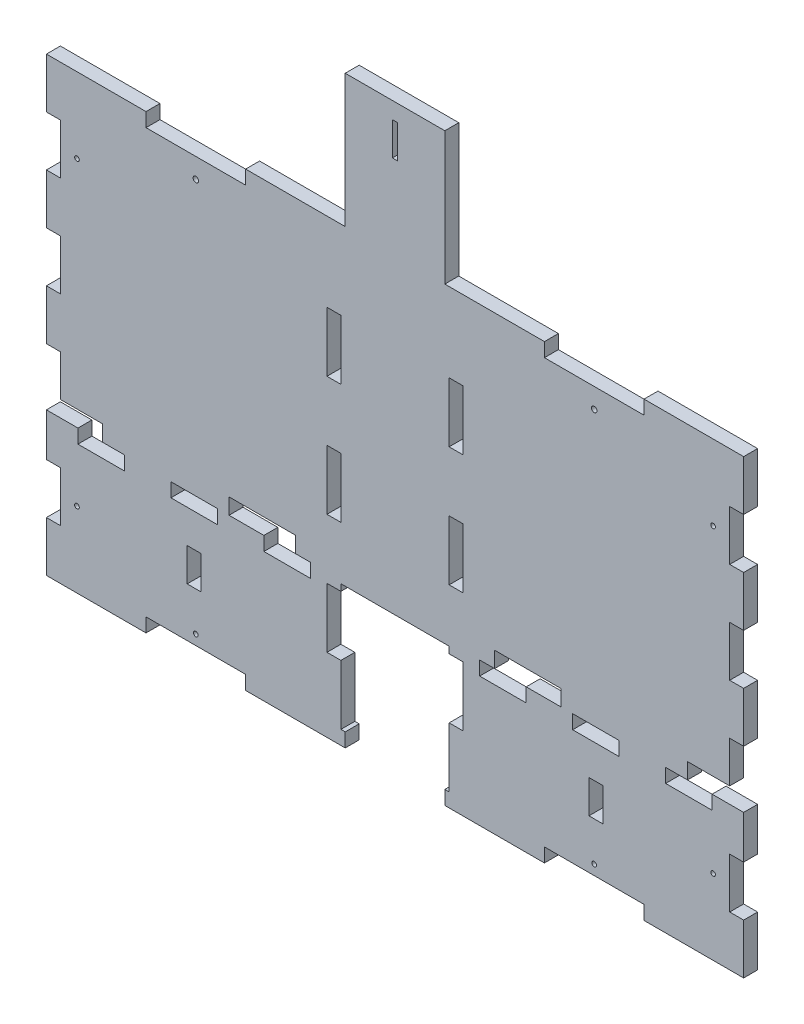
SolidWorks part; units mm, degrees
ref_plane "Front Plane" through (0, 0, 0) normal (0, 0, 1) x (1, 0, 0)
ref_plane "Top Plane" through (0, 0, 0) normal (0, 1, 0) x (1, 0, 0)
ref_plane "Right Plane" through (0, 0, 0) normal (1, 0, 0) x (0, 0, -1)
sketch "Sketch1" plane through (0, 0, 0) normal (0, 0, 1) x (1, 0, 0)
  line L1 (-127.8759, 88.4641) -> (138.8241, 88.4641)
  line L2 (-127.8759, 88.4641) -> (-127.8759, -84.2559)
  line L3 (-127.8759, -84.2559) -> (138.8241, -84.2559)
  line L4 (138.8241, 88.4641) -> (138.8241, -84.2559)
  dimension "D1" = 266.7
  dimension "D2" = 172.72
extrude "Boss-Extrude1" add sketch "Sketch1" along normal blind 5.334
sketch "Sketch2" plane through (0, 0, 5.334) normal (0, 0, 1) x (1, 0, 0)
  line L0 (-127.8759, -84.2559) -> (138.8241, -84.2559) construction
  line L1 (-89.7759, -84.2559) -> (-51.6759, -84.2559)
  line L2 (-89.7759, -84.2559) -> (-89.7759, -78.9219)
  line L3 (-89.7759, -78.9219) -> (-51.6759, -78.9219)
  line L4 (-51.6759, -84.2559) -> (-51.6759, -78.9219)
  line L5 (-89.7759, -78.9219) -> (-127.8759, -78.9219) construction
  line L6 (-13.5759, -84.2559) -> (24.5241, -84.2559)
  line L7 (-13.5759, -84.2559) -> (-13.5759, -78.9219)
  line L8 (-13.5759, -78.9219) -> (24.5241, -78.9219)
  line L9 (24.5241, -84.2559) -> (24.5241, -78.9219)
  line L10 (62.6241, -84.2559) -> (100.7241, -84.2559)
  line L11 (62.6241, -84.2559) -> (62.6241, -78.9219)
  line L12 (62.6241, -78.9219) -> (100.7241, -78.9219)
  line L13 (100.7241, -84.2559) -> (100.7241, -78.9219)
  line L14 (-127.8759, 88.4641) -> (-127.8759, -84.2559) construction
  line L15 (-51.6759, -78.9219) -> (-13.5759, -78.9219) construction
  line L16 (24.5241, -78.9219) -> (62.6241, -78.9219) construction
  line L17 (62.6241, -78.9219) -> (62.364, -79.7896) construction
  line L18 (100.7241, -78.9219) -> (138.8241, -78.9219) construction
  line L19 (138.8241, -84.2559) -> (138.8241, 88.4641) construction
  line L20 (-127.8759, 2.1041) -> (138.8241, 2.1041) construction
  line L21 (100.7241, 88.4641) -> (100.7241, 83.1301)
  line L22 (62.6241, 83.1301) -> (100.7241, 83.1301)
  line L23 (62.6241, 88.4641) -> (62.6241, 83.1301)
  line L24 (24.5241, 88.4641) -> (24.5241, 83.1301)
  line L25 (-13.5759, 83.1301) -> (24.5241, 83.1301)
  line L26 (-13.5759, 88.4641) -> (-13.5759, 83.1301)
  line L27 (-51.6759, 88.4641) -> (-51.6759, 83.1301)
  line L28 (-89.7759, 83.1301) -> (-51.6759, 83.1301)
  line L29 (-89.7759, 88.4641) -> (-89.7759, 83.1301)
  line L30 (62.6241, 88.4641) -> (100.7241, 88.4641)
  line L31 (-13.5759, 88.4641) -> (24.5241, 88.4641)
  line L32 (-89.7759, 88.4641) -> (-51.6759, 88.4641)
  dimension "D1" = 5.334
extrude "Cut-Extrude1" cut sketch "Sketch2" against normal through all
sketch "Sketch5" plane through (0, 0, 5.334) normal (0, 0, 1) x (1, 0, 0)
  line L0 (5.4741, 83.1301) -> (5.4741, -78.9219) construction
  line L1 (-13.5759, 83.1301) -> (24.5241, 83.1301) construction
  line L2 (24.5241, -78.9219) -> (-13.5759, -78.9219) construction
  line L3 (43.5741, -23.2959) -> (43.5741, -29.3919)
  line L4 (-58.0259, -23.2959) -> (-32.6259, -23.2959)
  line L5 (-58.0259, -23.2959) -> (-58.0259, -29.3919)
  line L6 (-58.0259, -29.3919) -> (-32.6259, -29.3919)
  line L7 (-32.6259, -23.2959) -> (-32.6259, -29.3919)
  line L8 (68.9741, -29.3919) -> (43.5741, -29.3919)
  line L9 (68.9741, -23.2959) -> (68.9741, -29.3919)
  line L10 (68.9741, -23.2959) -> (43.5741, -23.2959)
  line L11 (43.5741, -23.2959) -> (-32.6259, -23.2959) construction
  line L12 (-32.6259, -29.3919) -> (43.5741, -29.3919) construction
  line L13 (-127.8759, 88.4641) -> (-127.8759, -84.2559) construction
  line L14 (-106.3983, -23.2959) -> (-127.8759, -23.2959)
  line L15 (-106.3983, -23.2959) -> (-106.3983, -29.3919)
  line L16 (-106.3983, -29.3919) -> (-127.8759, -29.3919)
  line L17 (-127.8759, -23.2959) -> (-127.8759, -29.3919)
  line L18 (117.3465, -29.3919) -> (138.8241, -29.3919)
  line L19 (138.8241, -23.2959) -> (138.8241, -29.3919)
  line L20 (117.3465, -23.2959) -> (138.8241, -23.2959)
  line L21 (117.3465, -23.2959) -> (117.3465, -29.3919)
  line L22 (-51.6759, -78.9219) -> (-89.7759, -78.9219) construction
  dimension "D2" = 25.4
  dimension "D3" = 38.1
  dimension "D1" = 6.096
  dimension "D4" = 49.53
  dimension "D5" = 0
  dimension "D6" = 0
extrude "Cut-Extrude3" cut sketch "Sketch5" against normal through all
sketch "Sketch9" plane through (0, 0, 5.334) normal (0, 0, 1) x (1, 0, 0)
  line L0 (-127.8759, 88.4641) -> (-127.8759, -23.2959) construction
  line L1 (-127.8759, -65.0647) -> (-122.5419, -65.0647)
  line L2 (-127.8759, -65.0647) -> (-127.8759, -45.8736)
  line L3 (-127.8759, -45.8736) -> (-122.5419, -45.8736)
  line L4 (-122.5419, -65.0647) -> (-122.5419, -45.8736)
  line L5 (-122.5419, 69.273) -> (-122.5419, 88.4641) construction
  line L6 (-127.8759, -26.6825) -> (-122.5419, -26.6825)
  line L7 (-127.8759, -26.6825) -> (-127.8759, -7.4914)
  line L8 (-127.8759, -7.4914) -> (-122.5419, -7.4914)
  line L9 (-122.5419, -26.6825) -> (-122.5419, -7.4914)
  line L10 (-127.8759, 11.6997) -> (-122.5419, 11.6997)
  line L11 (-127.8759, 11.6997) -> (-127.8759, 30.8908)
  line L12 (-127.8759, 30.8908) -> (-122.5419, 30.8908)
  line L13 (-122.5419, 11.6997) -> (-122.5419, 30.8908)
  line L14 (-127.8759, 50.0819) -> (-122.5419, 50.0819)
  line L15 (-127.8759, 50.0819) -> (-127.8759, 69.273)
  line L16 (-127.8759, 69.273) -> (-122.5419, 69.273)
  line L17 (-122.5419, 50.0819) -> (-122.5419, 69.273)
  line L18 (-89.7759, 88.4641) -> (-127.8759, 88.4641) construction
  line L19 (-122.5419, 50.0819) -> (-122.5419, 30.8908) construction
  line L20 (-122.5419, 11.6997) -> (-122.5419, -7.4914) construction
  line L21 (-122.5419, -26.6825) -> (-122.5419, -45.8736) construction
  line L22 (-122.5419, -65.0647) -> (-122.5419, -84.2559) construction
  line L23 (-127.8759, -84.2559) -> (-89.7759, -84.2559) construction
  line L24 (5.4741, 83.1301) -> (5.4741, -78.9219) construction
  line L25 (-13.5759, 83.1301) -> (24.5241, 83.1301) construction
  line L26 (24.5241, -78.9219) -> (-13.5759, -78.9219) construction
  line L27 (133.4901, -65.0647) -> (133.4901, -84.2559) construction
  line L28 (133.4901, -26.6825) -> (133.4901, -45.8736) construction
  line L29 (133.4901, 11.6997) -> (133.4901, -7.4914) construction
  line L30 (133.4901, 50.0819) -> (133.4901, 30.8908) construction
  line L31 (133.4901, 69.273) -> (133.4901, 88.4641) construction
  line L32 (133.4901, 50.0819) -> (133.4901, 69.273)
  line L33 (138.8241, 69.273) -> (133.4901, 69.273)
  line L34 (138.8241, 50.0819) -> (138.8241, 69.273)
  line L35 (138.8241, 50.0819) -> (133.4901, 50.0819)
  line L36 (133.4901, 11.6997) -> (133.4901, 30.8908)
  line L37 (138.8241, 30.8908) -> (133.4901, 30.8908)
  line L38 (138.8241, 11.6997) -> (138.8241, 30.8908)
  line L39 (138.8241, 11.6997) -> (133.4901, 11.6997)
  line L40 (133.4901, -26.6825) -> (133.4901, -7.4914)
  line L41 (138.8241, -7.4914) -> (133.4901, -7.4914)
  line L42 (138.8241, -26.6825) -> (138.8241, -7.4914)
  line L43 (138.8241, -26.6825) -> (133.4901, -26.6825)
  line L44 (133.4901, -65.0647) -> (133.4901, -45.8736)
  line L45 (138.8241, -45.8736) -> (133.4901, -45.8736)
  line L46 (138.8241, -65.0647) -> (138.8241, -45.8736)
  line L47 (138.8241, -65.0647) -> (133.4901, -65.0647)
  dimension "D1" = 5.334
extrude "Cut-Extrude7" cut sketch "Sketch9" against normal through all
sketch "Sketch10" plane through (0, 88.4641, 0) normal (0, 1, 0) x (1, 0, 0)
  line L1 (24.5241, -5.334) -> (62.6241, -5.334)
  line L2 (24.5241, -5.334) -> (24.5241, 0)
  line L3 (24.5241, 0) -> (62.6241, 0)
  line L4 (62.6241, -5.334) -> (62.6241, 0)
extrude "Boss-Extrude2" add sketch "Sketch10" along normal blind 50.8
sketch "Sketch11" plane through (0, 0, 0) normal (0, 0, -1) x (-1, 0, 0)
  line L0 (-24.5241, 83.1301) -> (-24.5241, 139.2641) construction
  line L1 (-24.5241, 88.4641) -> (-31.1281, 88.4641)
  line L2 (-24.5241, 88.4641) -> (-24.5241, 129.1041)
  line L3 (-24.5241, 129.1041) -> (-31.1281, 129.1041)
  line L4 (-31.1281, 88.4641) -> (-31.1281, 129.1041)
  line L5 (13.5759, 88.4641) -> (51.6759, 88.4641) construction
  dimension "D1" = 6.604
  dimension "D2" = 40.64
  dimension "D3" = 0
extrude "Cut-Extrude8" cut sketch "Sketch11" against normal through all
sketch "Sketch12" plane through (0, 0, 5.334) normal (0, 0, 1) x (1, 0, 0)
  line L0 (62.6241, 139.2641) -> (62.6241, 83.1301) construction
  circle A0 centre (43.5741, 130.4765) radius 3.81
  dimension "D1" = 19.05
extrude "Cut-Extrude9" cut sketch "Sketch12" against normal through all
sketch "Sketch15" plane through (0, 0, 5.334) normal (0, 0, 1) x (1, 0, 0)
  line L1 (31.1281, 129.1041) -> (24.5241, 129.1041)
  line L2 (31.1281, 129.1041) -> (31.1281, 139.2641)
  line L3 (31.1281, 139.2641) -> (24.5241, 139.2641)
  line L4 (24.5241, 129.1041) -> (24.5241, 139.2641)
extrude "Cut-Extrude12" cut sketch "Sketch15" against normal through all
sketch "Sketch18" plane through (0, 0, 5.334) normal (0, 0, 1) x (1, 0, 0)
  line L0 (24.5241, 83.1301) -> (24.5241, 148.9274) construction
  line L1 (31.1281, 139.2641) -> (62.6241, 139.2641) construction
  line L2 (-13.5759, 83.1301) -> (24.5241, 83.1301)
  line L3 (-13.5759, 83.1301) -> (-13.5759, 139.2641)
  line L4 (-13.5759, 139.2641) -> (24.5241, 139.2641)
  line L5 (24.5241, 83.1301) -> (24.5241, 139.2641)
  dimension "D1" = 0
extrude "Boss-Extrude3" add sketch "Sketch18" against normal blind 5.334
sketch "Sketch19" plane through (0, 0, 5.334) normal (0, 0, 1) x (1, 0, 0)
  line L1 (31.1281, 88.4641) -> (65.8849, 88.4641)
  line L2 (31.1281, 88.4641) -> (31.1281, 143.4078)
  line L3 (31.1281, 143.4078) -> (65.8849, 143.4078)
  line L4 (65.8849, 88.4641) -> (65.8849, 143.4078)
extrude "Cut-Extrude15" cut sketch "Sketch19" against normal through all
sketch "Sketch21" plane through (0, 0, 5.334) normal (0, 0, 1) x (1, 0, 0)
  line L0 (133.4901, 59.6775) -> (-122.5419, 59.6775) construction
  line L1 (133.4901, 69.273) -> (133.4901, 50.0819) construction
  line L2 (-122.5419, 50.0819) -> (-122.5419, 69.273) construction
  line L3 (-122.5419, -55.4692) -> (133.4901, -55.4692) construction
  line L4 (-122.5419, -65.0647) -> (-122.5419, -45.8736) construction
  line L5 (133.4901, -45.8736) -> (133.4901, -65.0647) construction
  line L6 (138.8241, 2.1041) -> (-127.8759, 2.1041) construction
  line L7 (138.8241, -7.4914) -> (138.8241, 11.6997) construction
  line L8 (-127.8759, 11.6997) -> (-127.8759, -7.4914) construction
  line L9 (5.4741, 139.2641) -> (5.4741, -78.9219) construction
  line L10 (24.5241, 139.2641) -> (-13.5759, 139.2641) construction
  line L11 (24.5241, -78.9219) -> (-13.5759, -78.9219) construction
  circle A0 centre (127.1401, 59.6775) radius 0.889
  circle A1 centre (-116.1919, 59.6775) radius 0.889
  circle A2 centre (-116.1919, -55.4692) radius 0.889
  circle A3 centre (127.1401, -55.4692) radius 0.889
  dimension "D1" = 1.778
  dimension "D2" = 0
  dimension "D3" = 6.35
extrude "Cut-Extrude17" cut sketch "Sketch21" against normal through all
sketch "Sketch23" plane through (0, 0, 0) normal (0, 0, -1) x (-1, 0, 0)
  line L0 (-81.6741, 83.1301) -> (-81.6741, 61.0847) construction
  line L1 (-62.6241, 83.1301) -> (-100.7241, 83.1301) construction
  line L2 (-5.4741, 139.2641) -> (-5.4741, 93.6801) construction
  line L3 (-24.5241, 139.2641) -> (13.5759, 139.2641) construction
  circle A0 centre (-81.6741, 75.5101) radius 1.0477
  circle A1 centre (70.7259, 75.5101) radius 1.0477
  dimension "D1" = 2.0955
  dimension "D2" = 0
  dimension "D3" = 7.62
extrude "Cut-Extrude19" cut sketch "Sketch23" against normal through all
sketch "Sketch25" plane through (0, 0, 0) normal (0, 0, -1) x (-1, 0, 0)
  line L1 (-126.7591, -29.3919) -> (-108.9791, -29.3919)
  line L2 (-126.7591, -29.3919) -> (-126.7591, -34.7259)
  line L3 (-126.7591, -34.7259) -> (-108.9791, -34.7259)
  line L4 (-108.9791, -29.3919) -> (-108.9791, -34.7259)
  line L5 (-138.8241, -45.8736) -> (-138.8241, -29.3919) construction
  line L6 (-91.1991, -34.7259) -> (-73.4191, -34.7259)
  line L7 (-73.4191, -29.3919) -> (-73.4191, -34.7259)
  line L8 (-91.1991, -29.3919) -> (-73.4191, -29.3919)
  line L9 (-91.1991, -29.3919) -> (-91.1991, -34.7259)
  line L10 (-55.6391, -34.7259) -> (-37.8591, -34.7259)
  line L11 (-37.8591, -29.3919) -> (-37.8591, -34.7259)
  line L12 (-55.6391, -29.3919) -> (-37.8591, -29.3919)
  line L13 (-55.6391, -29.3919) -> (-55.6391, -34.7259)
  line L14 (-5.4741, -78.9219) -> (-5.4741, 139.2641) construction
  line L15 (-24.5241, -78.9219) -> (13.5759, -78.9219) construction
  line L16 (-24.5241, 139.2641) -> (13.5759, 139.2641) construction
  line L17 (44.6909, -29.3919) -> (44.6909, -34.7259)
  line L18 (44.6909, -29.3919) -> (26.9109, -29.3919)
  line L19 (26.9109, -29.3919) -> (26.9109, -34.7259)
  line L20 (44.6909, -34.7259) -> (26.9109, -34.7259)
  line L21 (115.8109, -29.3919) -> (98.0309, -29.3919)
  line L22 (115.8109, -29.3919) -> (115.8109, -34.7259)
  line L23 (115.8109, -34.7259) -> (98.0309, -34.7259)
  line L24 (98.0309, -29.3919) -> (98.0309, -34.7259)
  line L25 (80.2509, -29.3919) -> (80.2509, -34.7259)
  line L26 (80.2509, -29.3919) -> (62.4709, -29.3919)
  line L27 (62.4709, -29.3919) -> (62.4709, -34.7259)
  line L28 (80.2509, -34.7259) -> (62.4709, -34.7259)
  line L29 (-43.5741, -29.3919) -> (-68.9741, -29.3919) construction
  dimension "D5" = 0
  dimension "D1" = 12.065
  dimension "D2" = 17.78
  dimension "D3" = 5.334
  dimension "D4" = 3
extrude "Cut-Extrude20" cut sketch "Sketch25" against normal through all
sketch "Sketch26" plane through (0, 0, 0) normal (0, 0, -1) x (-1, 0, 0)
  line L0 (-91.1991, -34.7259) -> (-73.4191, -34.7259) construction
  line L1 (-84.9761, -47.4259) -> (-79.6421, -47.4259)
  line L2 (-84.9761, -47.4259) -> (-84.9761, -60.1259)
  line L3 (-84.9761, -60.1259) -> (-79.6421, -60.1259)
  line L4 (-79.6421, -47.4259) -> (-79.6421, -60.1259)
  line L5 (-82.3091, -34.7259) -> (-82.3091, -84.0309) construction
  line L6 (-5.4741, -78.9219) -> (-5.4741, -42.666) construction
  line L7 (-24.5241, -78.9219) -> (13.5759, -78.9219) construction
  line L8 (68.6939, -47.4259) -> (68.6939, -60.1259)
  line L9 (74.0279, -60.1259) -> (68.6939, -60.1259)
  line L10 (74.0279, -47.4259) -> (74.0279, -60.1259)
  line L11 (74.0279, -47.4259) -> (68.6939, -47.4259)
  point P4 (-82.3091, -34.7259)
  dimension "D3" = 5.334
  dimension "D1" = 12.7
  dimension "D2" = 12.7
  dimension "D4" = 2.667
extrude "Cut-Extrude21" cut sketch "Sketch26" against normal through all
sketch "Sketch27" plane through (0, 0, 0) normal (0, 0, -1) x (-1, 0, 0)
  line L0 (-24.5241, -78.9219) -> (13.5759, -78.9219) construction
  line L1 (-26.1751, -78.9219) -> (15.2269, -78.9219)
  line L2 (-26.1751, -78.9219) -> (-26.1751, -30.6619)
  line L3 (-26.1751, -30.6619) -> (15.2269, -30.6619)
  line L4 (15.2269, -78.9219) -> (15.2269, -30.6619)
  line L5 (13.5759, -82.3391) -> (-24.5241, -82.3391) construction
  line L6 (13.5759, -78.9219) -> (13.5759, -84.2559) construction
  line L7 (-24.5241, -84.2559) -> (-24.5241, -78.9219) construction
  line L8 (-5.4741, -82.3391) -> (-5.4741, 2.254) construction
  dimension "D1" = 41.402
  dimension "D2" = 48.26
  dimension "D3" = 0
  dimension "D4" = 20.701
extrude "Cut-Extrude22" cut sketch "Sketch27" against normal through all
sketch "Sketch28" plane through (0, 0, 0) normal (0, 0, -1) x (-1, 0, 0)
  line L0 (-26.1751, -30.6619) -> (-26.1751, -78.9219) construction
  line L1 (-26.1751, -56.0619) -> (-31.5091, -56.0619)
  line L2 (-26.1751, -56.0619) -> (-26.1751, -33.2019)
  line L3 (-26.1751, -33.2019) -> (-31.5091, -33.2019)
  line L4 (-31.5091, -56.0619) -> (-31.5091, -33.2019)
  line L5 (-26.1751, -78.9219) -> (-37.6658, -78.9219) construction
  line L6 (-26.1751, -10.3419) -> (-31.5091, -10.3419)
  line L7 (-26.1751, -10.3419) -> (-26.1751, 12.5181)
  line L8 (-26.1751, 12.5181) -> (-31.5091, 12.5181)
  line L9 (-31.5091, -10.3419) -> (-31.5091, 12.5181)
  line L10 (-26.1751, 35.3781) -> (-31.5091, 35.3781)
  line L11 (-26.1751, 35.3781) -> (-26.1751, 58.2381)
  line L12 (-26.1751, 58.2381) -> (-31.5091, 58.2381)
  line L13 (-31.5091, 35.3781) -> (-31.5091, 58.2381)
  line L14 (-31.5091, -56.0619) -> (-31.5091, -78.9219) construction
  line L15 (-31.5091, -33.2019) -> (-31.5091, -10.3419) construction
  line L16 (-31.5091, 12.5181) -> (-31.5091, 35.3781) construction
  line L17 (-5.4741, -30.6619) -> (-5.4741, 67.0594) construction
  line L18 (15.2269, -30.6619) -> (-26.1751, -30.6619) construction
  line L19 (20.5609, 12.5181) -> (20.5609, 35.3781) construction
  line L20 (20.5609, -33.2019) -> (20.5609, -10.3419) construction
  line L21 (20.5609, 35.3781) -> (20.5609, 58.2381)
  line L22 (15.2269, 58.2381) -> (20.5609, 58.2381)
  line L23 (15.2269, 35.3781) -> (15.2269, 58.2381)
  line L24 (15.2269, 35.3781) -> (20.5609, 35.3781)
  line L25 (20.5609, -10.3419) -> (20.5609, 12.5181)
  line L26 (15.2269, 12.5181) -> (20.5609, 12.5181)
  line L27 (15.2269, -10.3419) -> (15.2269, 12.5181)
  line L28 (15.2269, -10.3419) -> (20.5609, -10.3419)
  line L29 (20.5609, -56.0619) -> (20.5609, -33.2019)
  line L30 (15.2269, -33.2019) -> (20.5609, -33.2019)
  line L31 (15.2269, -56.0619) -> (15.2269, -33.2019)
  line L32 (15.2269, -56.0619) -> (20.5609, -56.0619)
  line L33 (-26.1751, 35.3781) -> (-26.1751, 12.5181) construction
  line L34 (-26.1751, -10.3419) -> (-26.1751, -33.2019) construction
  dimension "D1" = 22.86
  dimension "D2" = 22.86
  dimension "D3" = 22.86
  dimension "D4" = 22.86
  dimension "D5" = 22.86
  dimension "D6" = 22.86
  dimension "D7" = 5.334
extrude "Cut-Extrude23" cut sketch "Sketch28" against normal through all
sketch "Sketch29" plane through (0, 0, 0) normal (0, 0, -1) x (-1, 0, 0)
  line L0 (-100.7241, -78.9219) -> (-62.6241, -78.9219) construction
  line L1 (-81.6741, -78.9219) -> (-81.6741, -69.05) construction
  line L2 (-5.4741, -30.6619) -> (-5.4741, -7.7704) construction
  line L3 (15.2269, -30.6619) -> (-26.1751, -30.6619) construction
  circle A0 centre (-81.6741, -75.1119) radius 0.889
  circle A1 centre (70.7259, -75.1119) radius 0.889
  dimension "D1" = 1.778
  dimension "D2" = 3.81
  dimension "D3" = 0
extrude "Cut-Extrude24" cut sketch "Sketch29" against normal through all
sketch "Sketch30" plane through (0, 0, 0) normal (0, 0, -1) x (-1, 0, 0)
  line L0 (-24.5241, 139.2641) -> (13.5759, 139.2641) construction
  line L1 (-6.4901, 132.9141) -> (-4.4581, 132.9141)
  line L2 (-6.4901, 132.9141) -> (-6.4901, 120.2141)
  line L3 (-6.4901, 120.2141) -> (-4.4581, 120.2141)
  line L4 (-4.4581, 132.9141) -> (-4.4581, 120.2141)
  line L5 (-5.4741, 139.2641) -> (-5.4741, 112.4981) construction
  dimension "D1" = 12.7
  dimension "D2" = 6.35
  dimension "D3" = 2.032
  dimension "D4" = 1.016
extrude "Cut-Extrude25" cut sketch "Sketch30" against normal through all
equation "\"MDF\"= .21in"
equation "\"Foamcore\"= .13in"
equation "\"Gmaterial\"= \"MDF\""
equation "\"D1@Boss-Extrude1\"=\"MDF\""
equation "\"D1@Sketch2\"=\"MDF\""
equation "\"D1@Sketch5\"=\"MDF\"+0.03"
equation "\"D1@Sketch9\"=\"MDF\""
equation "\"D1@Sketch11\"=\"MDF\"+.05"
equation "\"D1@Boss-Extrude3\"=\"MDF\""
equation "\"D3@Sketch25\"=\"MDF\""
equation "\"D3@Sketch26\"=\"MDF\""
equation "\"D4@Sketch26\"=\"MDF\"/2"
equation "\"D7@Sketch28\"=\"MDF\""
